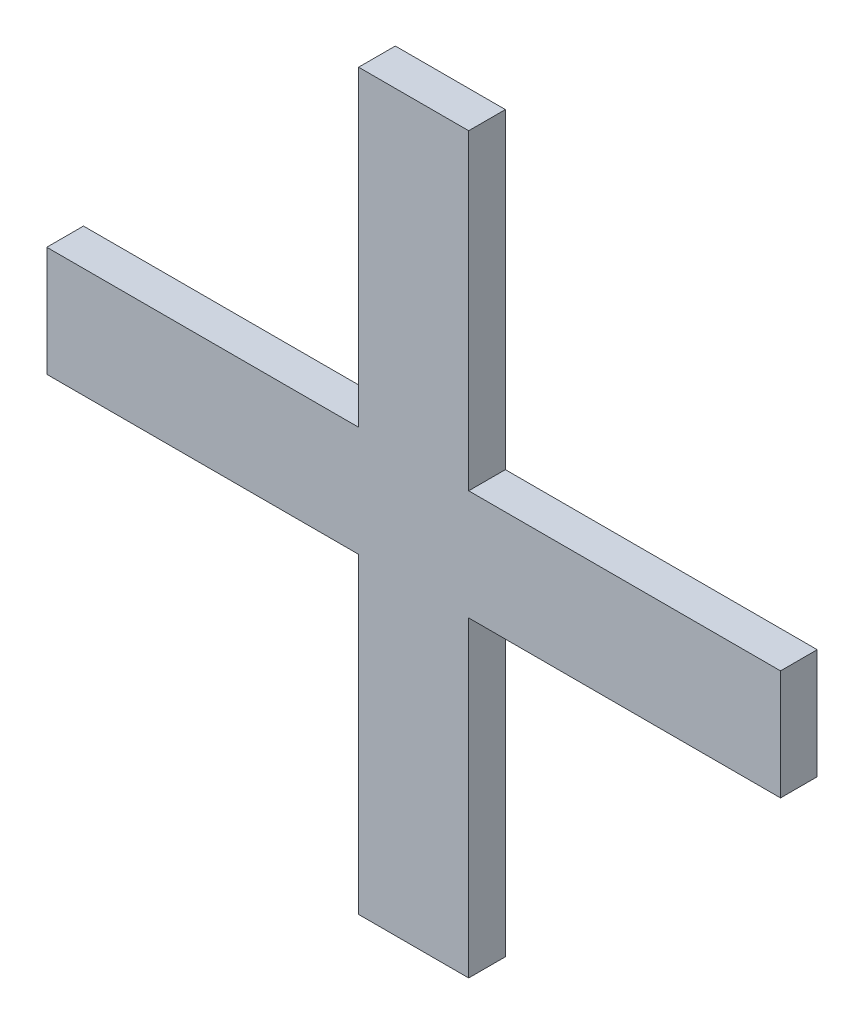
SolidWorks part; units mm, degrees
ref_plane "Front Plane" through (0, 0, 0) normal (0, 0, 1) x (1, 0, 0)
ref_plane "Top Plane" through (0, 0, 0) normal (0, 1, 0) x (1, 0, 0)
ref_plane "Right Plane" through (0, 0, 0) normal (1, 0, 0) x (0, 0, -1)
sketch "Sketch1" plane through (0, 0, 0) normal (0, 0, 1) x (1, 0, 0)
  line L1 (-4925.2727, -769.8182) -> (-4895.2727, -769.8182)
  line L2 (-4925.2727, -769.8182) -> (-4925.2727, -969.8182)
  line L3 (-4925.2727, -969.8182) -> (-4895.2727, -969.8182)
  line L4 (-4895.2727, -769.8182) -> (-4895.2727, -969.8182)
  dimension "D1" = 200
  dimension "D2" = 30
extrude "Boss-Extrude1" add sketch "Sketch1" along normal blind 10
sketch "Sketch2" plane through (0, 0, 0) normal (0, 0, 1) x (1, 0, 0)
  line L0 (-4895.2727, -769.8182) -> (-4925.2727, -769.8182) construction
  line L1 (-5010.2727, -854.8182) -> (-4810.2727, -854.8182)
  line L2 (-5010.2727, -854.8182) -> (-5010.2727, -884.8182)
  line L3 (-5010.2727, -884.8182) -> (-4810.2727, -884.8182)
  line L4 (-4810.2727, -854.8182) -> (-4810.2727, -884.8182)
  line L6 (-4925.2727, -769.8182) -> (-4925.2727, -969.8182) construction
  point P6 (-5010.2727, -869.8182)
  dimension "D1" = 200
  dimension "D2" = 30
  dimension "D3" = 85
  dimension "D4" = 85
extrude "Boss-Extrude2" add sketch "Sketch2" along normal blind 10
